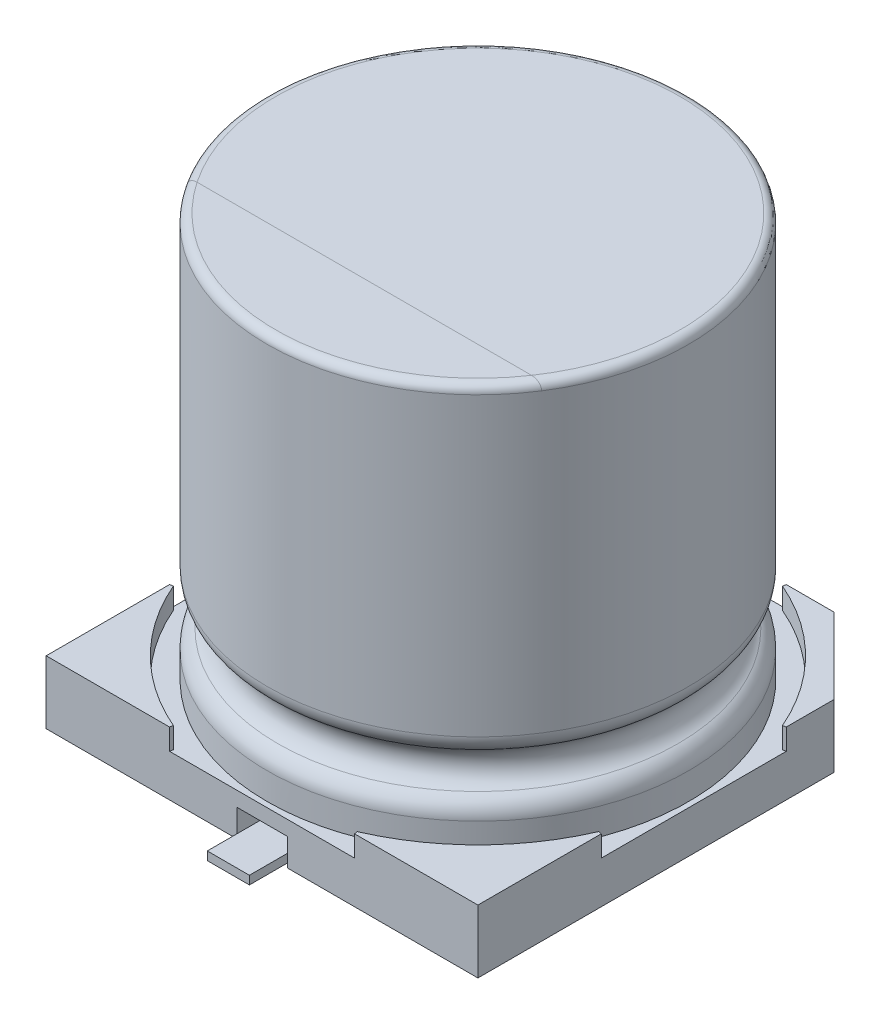
SolidWorks part; units mm, degrees
ref_plane "Front Plane" through (0, 0, 0) normal (0, 0, 1) x (1, 0, 0)
ref_plane "Top Plane" through (0, 0, 0) normal (0, 1, 0) x (1, 0, 0)
ref_plane "Right Plane" through (0, 0, 0) normal (1, 0, 0) x (0, 0, -1)
sketch "Sketch1" plane through (0, 0, 0) normal (0, 1, 0) x (1, 0, 0)
  line L1 (-5.125, 5.125) -> (5.125, 5.125)
  line L2 (-5.125, 5.125) -> (-5.125, -5.125)
  line L3 (-5.125, -5.125) -> (5.125, -5.125)
  line L4 (5.125, 5.125) -> (5.125, -5.125)
  line L5 (-5.125, 5.125) -> (5.125, -5.125) construction
  line L6 (-5.125, -5.125) -> (5.125, 5.125) construction
  point P0 (0, 0)
  dimension "D1" = 10.25
extrude "Boss-Extrude1" add sketch "Sketch1" along normal blind 1
sketch "Sketch2" plane through (0, 1, 0) normal (0, 1, 0) x (1, 0, 0)
  circle A0 centre (0, 0) radius 5
  dimension "D1" = 10
extrude "Boss-Extrude2" add sketch "Sketch2" along normal blind 9.6 separate body
sketch "Sketch5" plane through (0, 1, 0) normal (0, 1, 0) x (1, 0, 0)
  line L0 (-5.125, -1.9961) -> (-5.125, -5.125)
  line L1 (-5.125, 5.125) -> (-1.9961, 5.125)
  line L2 (-5.125, 5.125) -> (-5.125, 1.9961)
  line L3 (-5.125, -5.125) -> (-1.9961, -5.125)
  line L4 (5.125, 5.125) -> (5.125, 1.9961)
  line L5 (5.125, -1.9961) -> (5.125, -5.125)
  line L6 (1.9961, 5.125) -> (5.125, 5.125)
  line L7 (1.9961, -5.125) -> (5.125, -5.125)
  arc A0 (-5.125, -1.9961) -> (-1.9961, -5.125) centre (0, 0) ccw
  arc A1 (5.125, 1.9961) -> (1.9961, 5.125) centre (0, 0) ccw
  arc A2 (-1.9961, 5.125) -> (-5.125, 1.9961) centre (0, 0) ccw
  arc A3 (1.9961, -5.125) -> (5.125, -1.9961) centre (0, 0) ccw
  dimension "D1" = 11
extrude "Boss-Extrude3" add sketch "Sketch5" along normal blind 0.5
sketch "Sketch3" plane through (0, 0, 0) normal (0, 0, 1) x (1, 0, 0)
  line L0 (5, 1) -> (5, 2.5) construction
  circle A0 centre (5, 2.5) radius 0.5
  point P2 (5, 2)
  dimension "D1" = 1
  dimension "D2" = 1
revolve "Cut-Revolve1" cut sketch "Sketch3" angle 360 about axis through (0, 10.6, 0) along (0, -1, 0)
fillet "Fillet1" radius 0.5 2 edges at (0, 2, 5) (0, 3, -5)
fillet "Fillet2" radius 0.2 1 edges at (0, 10.6, 5)
chamfer "Chamfer1" distance 1.8 angle 45 2 edges at (5.125, 0.75, -5.125) (-5.125, 0.75, -5.125)
sketch "Sketch4" plane through (0, 0, 0) normal (0, -1, 0) x (1, 0, 0)
  line L0 (-5.125, 5.125) -> (5.125, 5.125) construction
  line L1 (-0.6, 5.125) -> (0.6, 5.125)
  line L2 (-0.6, 5.125) -> (-0.6, 3.925)
  line L3 (-0.6, 3.925) -> (0.6, 3.925)
  line L4 (0.6, 5.125) -> (0.6, 3.925)
  line L5 (0, 0) -> (-1.855, 0) construction
  line L6 (-0.6, -5.125) -> (-0.6, -3.925)
  line L7 (-0.6, -5.125) -> (0.6, -5.125)
  line L8 (0.6, -5.125) -> (0.6, -3.925)
  line L9 (-0.6, -3.925) -> (0.6, -3.925)
  point P10 (0, 5.125)
  dimension "D1" = 1.2
extrude "Cut-Extrude1" cut sketch "Sketch4" against normal blind 0.65
sketch "Sketch6" plane through (0, 0, 0) normal (1, 0, 0) x (0, 0, -1)
  line L0 (-5.925, 0) -> (-3.925, 0)
  dimension "D1" = 2
extrude "Extrude-Thin1" add sketch "Sketch6" along normal blind 0.5 and the other way blind 0.5 separate body thin thin type one direction reverse wall 0.2
mirror "Mirror3" about plane through (0, 0, 0) normal (0, 0, 1) of bodies 106
chamfer "Chamfer2" distance 0.2 angle 80 8 edges at (-1.9961, 1.25, 5.125) (-5.125, 1.25, 1.9961) (-5.125, 1.25, -1.9961) (-1.9961, 1.25, -5.125) (1.9961, 1.25, -5.125) (5.125, 1.25, -1.9961) (1.9961, 1.25, 5.125) (5.125, 1.25, 1.9961)
sketch "Sketch7" plane through (0, 10.6, 0) normal (0, 1, 0) x (1, 0, 0)
  line L0 (7.8215, -2.6968) -> (-7.8215, -2.6968)
  point P3 (0, -2.6968)
split line "Split Line1"
